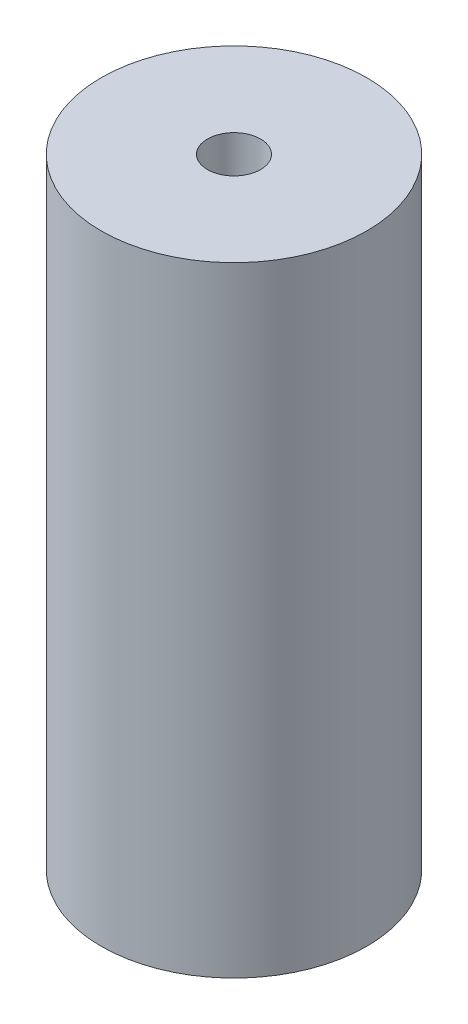
SolidWorks part; units mm, degrees
ref_plane "Front Plane" through (0, 0, 0) normal (0, 0, 1) x (1, 0, 0)
ref_plane "Top Plane" through (0, 0, 0) normal (0, 1, 0) x (1, 0, 0)
ref_plane "Right Plane" through (0, 0, 0) normal (1, 0, 0) x (0, 0, -1)
sketch "Sketch1" plane through (0, 0, 0) normal (0, 0, 1) x (1, 0, 0)
  line L0 (3, 30) -> (15, 30)
  line L1 (15, 30) -> (15, -40)
  line L2 (15, -40) -> (0, -40)
  line L3 (0, -40) -> (0, 0)
  line L4 (0, 0) -> (3, 0)
  line L5 (3, 0) -> (3, 30)
  dimension "D1" = 70
  dimension "D2" = 15
  dimension "D3" = 3
  dimension "D4" = 30
revolve "Revolve1" add sketch "Sketch1" angle 360 about L3
sketch "Sketch3" plane through (0, -40, 0) normal (0, -1, 0) x (1, 0, 0)
  line L0 (0, 0) -> (0, 9.5913) construction
  line L1 (-2.5, 12.1825) -> (-2.5, 9.6825)
  line L2 (-2.5, 12.1825) -> (2.5, 12.1825)
  line L3 (2.5, 12.1825) -> (2.5, 9.6825)
  arc A0 (-2.5, 9.6825) -> (2.5, 9.6825) centre (0, 0) ccw
  dimension "D1" = 20
  dimension "D2" = 2.5
  dimension "D3" = 5
extrude "Cut-Extrude2" cut sketch "Sketch3" against normal blind 30
sketch "Sketch6" plane through (0, 0, 0) normal (1, 0, 0) x (0, 0, -1)
  line L0 (-10, -10) -> (-10, -15)
  line L1 (-10, -15) -> (-12.5, -15)
  line L2 (-12.5, -15) -> (-12.5, -10)
  line L3 (-12.5, -10) -> (-10, -10)
  line L6 (-12.1825, -10) -> (-9.6825, -10) construction
  line L7 (0, 0) -> (0, -24.7484) construction
  dimension "D1" = 2.5
  dimension "D2" = 5
  dimension "D3" = 10
  dimension "D4" = 0
revolve "Cut-Revolve1" cut sketch "Sketch6" angle 50 about L7
